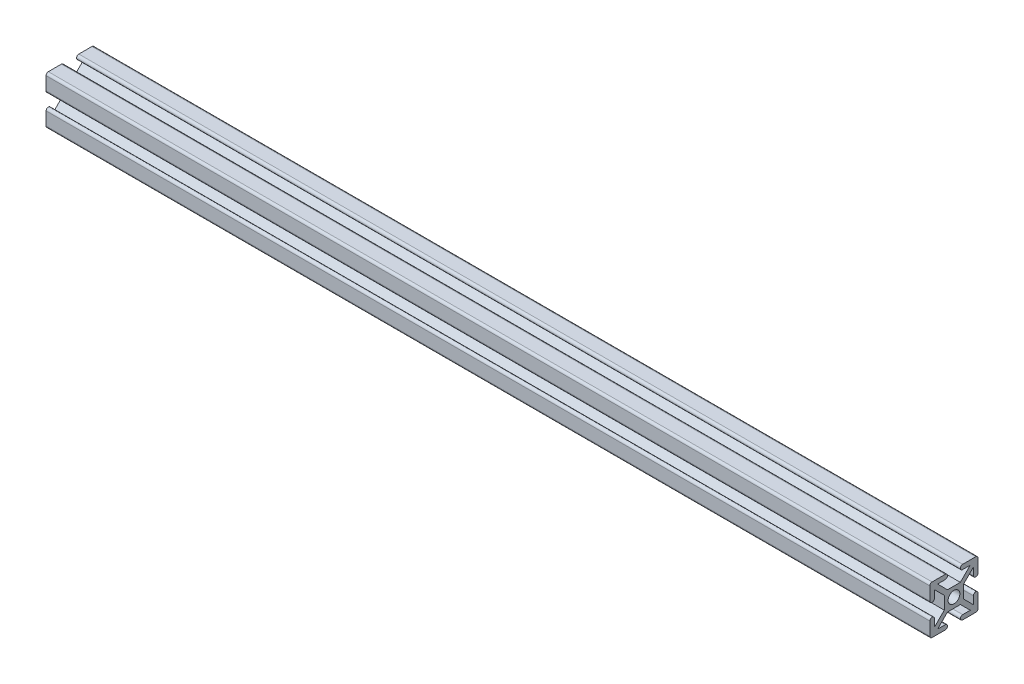
SolidWorks part; units mm, degrees
ref_plane "Front Plane" through (0, 0, 0) normal (0, 0, 1) x (1, 0, 0)
ref_plane "Top Plane" through (0, 0, 0) normal (0, 1, 0) x (1, 0, 0)
ref_plane "Right Plane" through (0, 0, 0) normal (1, 0, 0) x (0, 0, -1)
sketch "Sketch1" plane through (0, 0, 0) normal (1, 0, 0) x (0, 0, -1)
  line L0 (33.0708, 47.0243) -> (33.0708, 48.4493) construction
  line L1 (52.1237, 30.8743) -> (56.8487, 30.8743)
  line L2 (31.6458, 56.5992) -> (31.6458, 48.4493)
  line L3 (33.0708, 58.0242) -> (41.2208, 58.0242)
  line L4 (52.0708, 58.0242) -> (60.2208, 58.0242)
  line L5 (36.5487, 30.8743) -> (41.2737, 30.8743)
  line L6 (40.6458, 47.0243) -> (40.6458, 39.0243)
  line L7 (31.6987, 37.5993) -> (31.6987, 29.4493)
  line L8 (33.0973, 28.0507) -> (41.2737, 28.0243)
  line L9 (61.6458, 56.5992) -> (61.6458, 48.553)
  line L10 (34.4958, 53.1743) -> (34.4958, 48.4493)
  line L11 (61.6458, 37.703) -> (61.6458, 29.4493)
  line L12 (42.6458, 56.5992) -> (41.2208, 56.5992) construction
  line L13 (52.1237, 28.0243) -> (60.2208, 28.0243)
  line L14 (36.4958, 55.1742) -> (41.2208, 55.1742)
  line L15 (34.4958, 37.5993) -> (34.4958, 32.8743)
  line L16 (50.6458, 56.5992) -> (52.0708, 56.5992) construction
  line L17 (52.0708, 55.1742) -> (56.7958, 55.1742)
  line L18 (60.2208, 47.128) -> (60.2208, 48.553) construction
  line L19 (42.6458, 49.0242) -> (36.4958, 55.1742)
  line L20 (58.7958, 53.1742) -> (58.7958, 48.553)
  line L21 (60.2208, 39.128) -> (60.2208, 37.703) construction
  line L22 (40.6458, 47.0243) -> (34.4958, 53.1743)
  line L23 (58.7958, 37.703) -> (58.7958, 32.8742)
  line L24 (50.6987, 29.4493) -> (52.1237, 29.4493) construction
  line L25 (40.6458, 39.0243) -> (34.4958, 32.8743)
  line L26 (42.6458, 49.0242) -> (50.6458, 49.0242)
  line L27 (50.6458, 49.0242) -> (56.7958, 55.1742)
  line L28 (33.0973, 39.0243) -> (33.0973, 37.5993) construction
  line L29 (36.5487, 30.8743) -> (42.6987, 37.0243)
  line L30 (42.6987, 37.0243) -> (50.6987, 37.0243)
  line L31 (50.6987, 37.0243) -> (56.8487, 30.8743)
  line L32 (42.6987, 29.4493) -> (41.2737, 29.4493) construction
  line L33 (52.6458, 39.0242) -> (58.7958, 32.8742)
  line L34 (52.6458, 47.0242) -> (58.7958, 53.1742)
  line L35 (52.6458, 47.0242) -> (52.6458, 39.0242)
  circle A0 centre (46.6987, 43.0243) radius 3.645
  arc A1 (31.6458, 48.4493) -> (34.4958, 48.4493) centre (33.0708, 48.4493) ccw
  arc A2 (41.2208, 55.1742) -> (41.2208, 58.0242) centre (41.2208, 56.5992) ccw
  arc A3 (52.0708, 58.0242) -> (52.0708, 55.1742) centre (52.0708, 56.5992) ccw
  arc A4 (58.7958, 48.553) -> (61.6458, 48.553) centre (60.2208, 48.553) ccw
  arc A5 (61.6458, 37.703) -> (58.7958, 37.703) centre (60.2208, 37.703) ccw
  arc A6 (52.1237, 30.8743) -> (52.1237, 28.0243) centre (52.1237, 29.4493) ccw
  arc A7 (34.4958, 37.5993) -> (31.6987, 37.5993) centre (33.0973, 37.5993) ccw
  arc A8 (41.2737, 28.0243) -> (41.2737, 30.8743) centre (41.2737, 29.4493) ccw
  arc A9 (31.6987, 29.4493) -> (33.0973, 28.0507) centre (33.0973, 29.4493) ccw
  arc A10 (60.2208, 28.0243) -> (61.6458, 29.4493) centre (60.2208, 29.4493) ccw
  arc A11 (61.6458, 56.5992) -> (60.2208, 58.0242) centre (60.2208, 56.5992) ccw
  arc A12 (33.0708, 58.0242) -> (31.6458, 56.5992) centre (33.0708, 56.5992) ccw
  dimension "D1" = 1.425
  dimension "D2" = 1.425
  dimension "D3" = 1.425
  dimension "D4" = 1.425
  dimension "D5" = 1.425
  dimension "D6" = 1.425
extrude "Boss-Extrude1" add sketch "Sketch1" along normal blind 550
